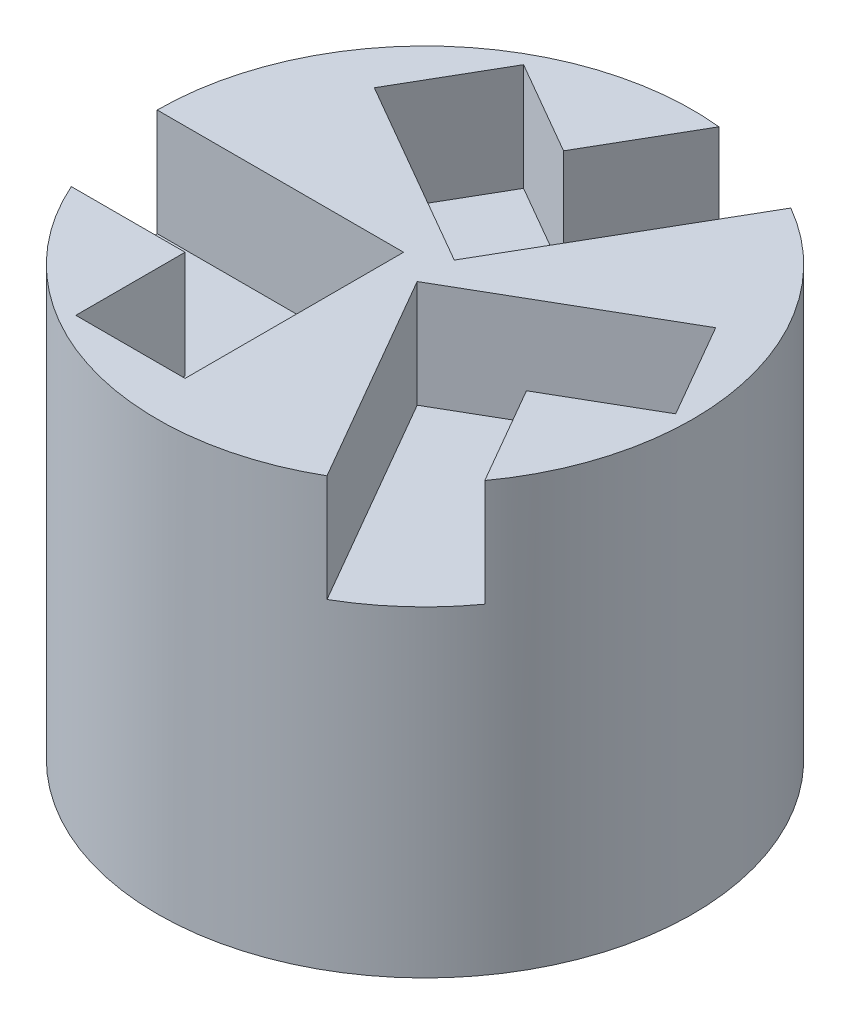
SolidWorks part; units mm, degrees
ref_plane "Front Plane" through (0, 0, 0) normal (0, 0, 1) x (1, 0, 0)
ref_plane "Top Plane" through (0, 0, 0) normal (0, 1, 0) x (1, 0, 0)
ref_plane "Right Plane" through (0, 0, 0) normal (1, 0, 0) x (0, 0, -1)
sketch "Sketch1" plane through (0, 0, 0) normal (0, 1, 0) x (1, 0, 0)
  circle A0 centre (0, 0) radius 25
  dimension "D1" = 50
extrude "Boss-Extrude1" add sketch "Sketch1" along normal blind 40
sketch "Sketch2" plane through (0, 40, 0) normal (0, 1, 0) x (1, 0, 0)
  line L0 (-25, 0) -> (-2, 0)
  line L1 (-2, 0) -> (-2, -20.4)
  line L2 (-2, -20.4) -> (-12.2, -20.4)
  line L3 (-12.2, -20.4) -> (-12.2, -10.2)
  line L4 (-12.2, -10.2) -> (-22.8245, -10.2)
  circle A0 centre (0, 0) radius 25 construction
  arc A1 (-25, 0) -> (-22.8245, -10.2) centre (0, 0) ccw
  point P10 (0, 0)
  dimension "D1" = 10.2
  dimension "D2" = 10.2
  dimension "D3" = 10.2
  dimension "D4" = 2
extrude "Cut-Extrude1" cut sketch "Sketch2" against normal blind 10
pattern_circular "CirPattern1" count 3 over 360 about axis through (0, 0, 0) along (0, 1, 0) of "Cut-Extrude1"
sketch "Sketch7" plane through (0, 0, 0) normal (0, -1, 0) x (1, 0, 0)
  circle A0 centre (0, 0) radius 15.1
  dimension "D1" = 30.2
extrude "Cut-Extrude3" cut sketch "Sketch7" against normal blind 8.7
equation "\"D3@Sketch2\"=\"D1@Sketch2\""
equation "\"D2@Sketch2\"=\"D1@Sketch2\""
